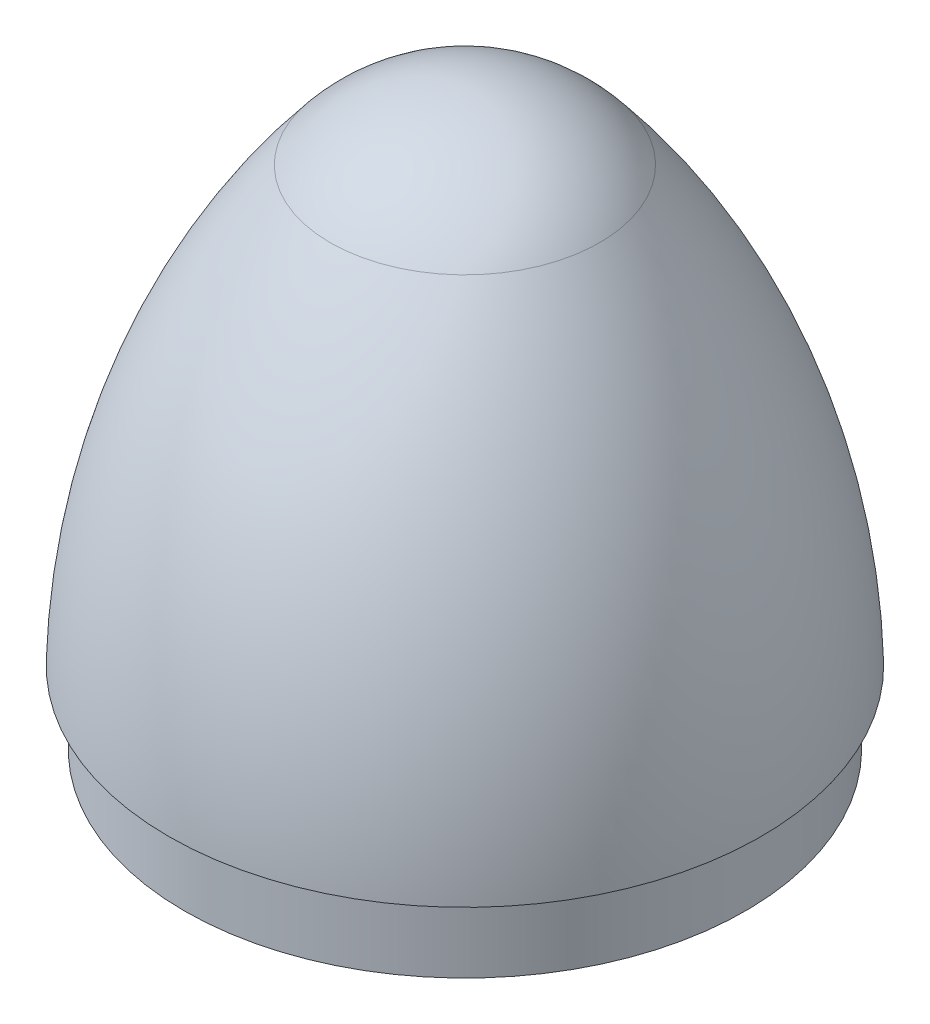
SolidWorks part; units mm, degrees
ref_plane "Front Plane" through (0, 0, 0) normal (0, 0, 1) x (1, 0, 0)
ref_plane "Top Plane" through (0, 0, 0) normal (0, 1, 0) x (1, 0, 0)
ref_plane "Right Plane" through (0, 0, 0) normal (1, 0, 0) x (0, 0, -1)
sketch "Sketch1" plane through (0, 0, 0) normal (0, 0, 1) x (1, 0, 0)
  line L0 (0, 85.6939) -> (0, -41.0108) construction
  line L1 (36, 0) -> (36, 9.2735)
  line L2 (36, 9.2735) -> (38, 9.2735)
  line L3 (33, 0) -> (33, 11.9714)
  line L4 (33, 11.9714) -> (35, 11.9714)
  line L5 (0, 73.0983) -> (0, 70.5026)
  line L6 (33, 0) -> (36, 0)
  arc A0 (38, 9.2735) -> (17.3014, 64.9302) centre (-53.4401, 6.9443) ccw
  arc A1 (17.3014, 64.9302) -> (0, 73.0983) centre (0.0446, 50.7851) ccw
  arc A2 (35, 11.9714) -> (15.5561, 62.7709) centre (-61.7472, 4.0615) ccw
  arc A3 (15.5561, 62.7709) -> (0, 70.5026) centre (-0.0248, 50.9377) ccw
  dimension "D1" = 2
  dimension "D2" = 36
  dimension "D3" = 33
  dimension "D4" = 2
revolve "Revolve1" add sketch "Sketch1" angle 360 about L0
